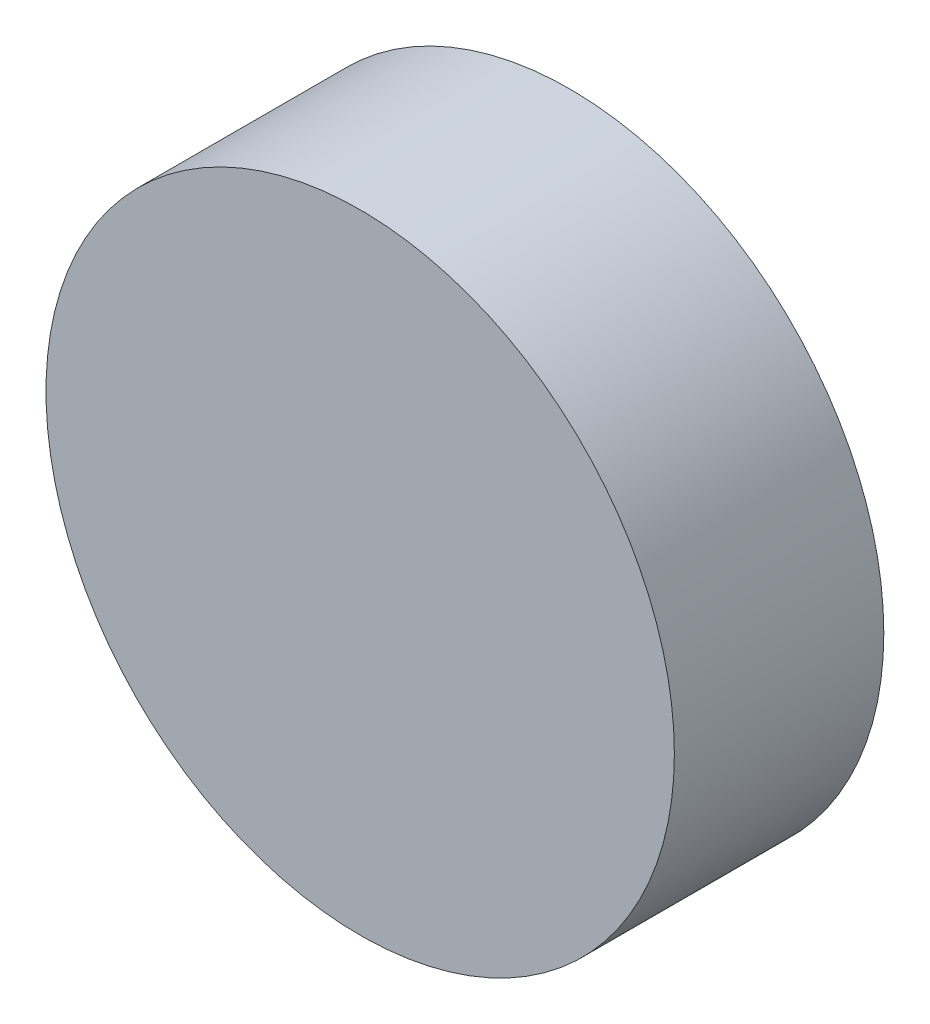
SolidWorks part; units mm, degrees
ref_plane "Front Plane" through (0, 0, 0) normal (0, 0, 1) x (1, 0, 0)
ref_plane "Top Plane" through (0, 0, 0) normal (0, 1, 0) x (1, 0, 0)
ref_plane "Right Plane" through (0, 0, 0) normal (1, 0, 0) x (0, 0, -1)
sketch "Diametric_magnet_D6_L2_Profile" plane through (0, 0, 0) normal (0, 0, 1) x (1, 0, 0)
  circle A0 centre (12.5, 0) radius 3
extrude "Diametric_magnet_D6_L2" add sketch "Diametric_magnet_D6_L2_Profile" along normal blind 2 from offset 18.8
